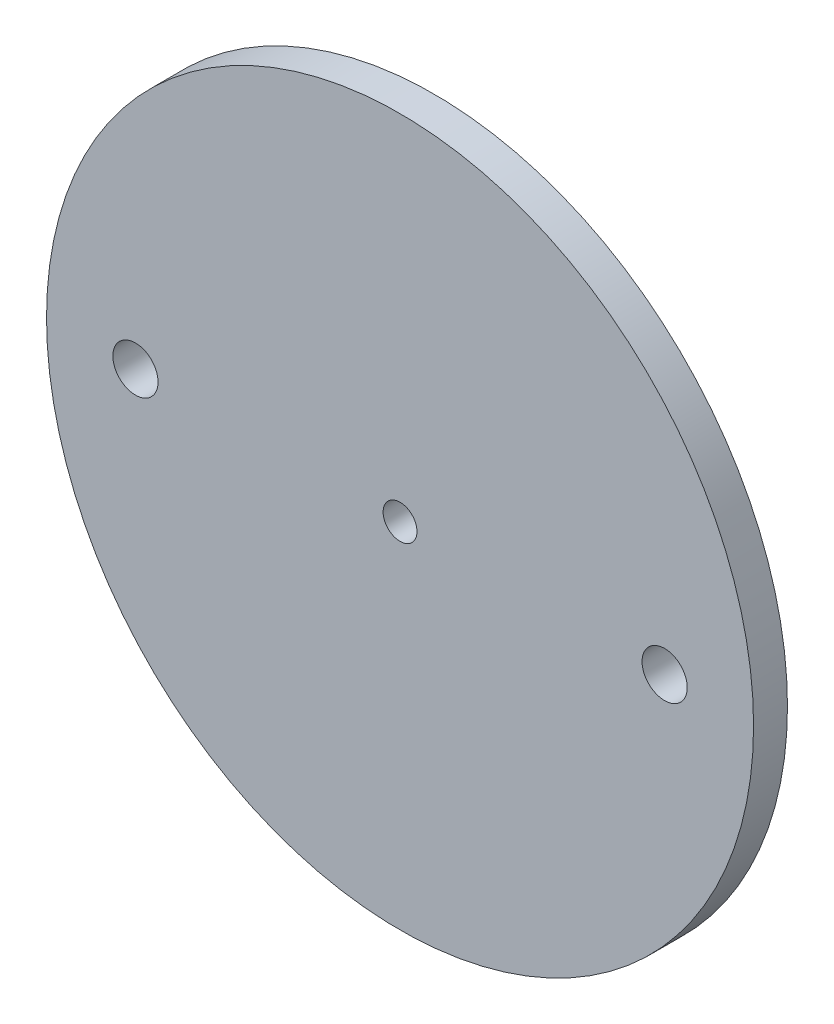
SolidWorks part; units mm, degrees
material "E-Glass Fiber"
ref_plane "Front Plane" through (0, 0, 0) normal (0, 0, 1) x (1, 0, 0)
ref_plane "Top Plane" through (0, 0, 0) normal (0, 1, 0) x (1, 0, 0)
ref_plane "Right Plane" through (0, 0, 0) normal (1, 0, 0) x (0, 0, -1)
sketch "Sketch1" plane through (0, 0, 0) normal (0, 0, 1) x (1, 0, 0)
  circle A0 centre (0, 0) radius 49.6697
  dimension "D1" = 99.3394
extrude "Boss-Extrude1" add sketch "Sketch1" along normal blind 4.7625
sketch "Sketch2" plane through (0, 0, 4.7625) normal (0, 0, 1) x (1, 0, 0)
  line L0 (37.1729, 0) -> (0, 0) construction
  line L1 (0, 0) -> (-37.1729, 0) construction
  circle A0 centre (0, 0) radius 2.3812
  circle A1 centre (37.1729, 0) radius 3.175
  circle A2 centre (-37.1729, 0) radius 3.175
  dimension "D1" = 4.7625
  dimension "D2" = 6.35
  dimension "D3" = 74.3458
extrude "Cut-Extrude1" cut sketch "Sketch2" against normal through all
